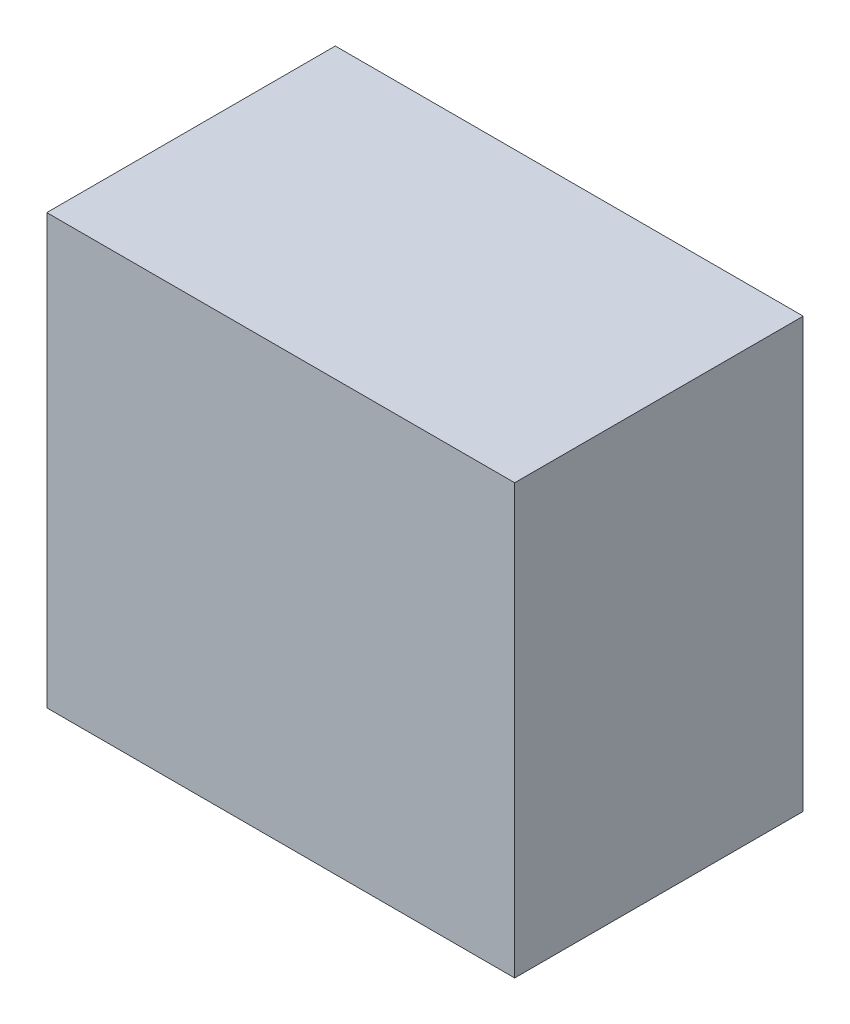
SolidWorks part; units mm, degrees
ref_plane "Alzado" through (0, 0, 0) normal (0, 0, 1) x (1, 0, 0)
ref_plane "Planta" through (0, 0, 0) normal (0, 1, 0) x (1, 0, 0)
ref_plane "Vista lateral" through (0, 0, 0) normal (1, 0, 0) x (0, 0, -1)
sketch "Croquis1" plane through (0, 0, 0) normal (0, 0, 1) x (1, 0, 0)
  line L1 (0, 0) -> (600, 0)
  line L2 (0, 0) -> (0, 550)
  line L3 (0, 550) -> (600, 550)
  line L4 (600, 0) -> (600, 550)
  dimension "D1" = 600
  dimension "D2" = 550
extrude "Saliente-Extruir1" add sketch "Croquis1" along normal blind 370
